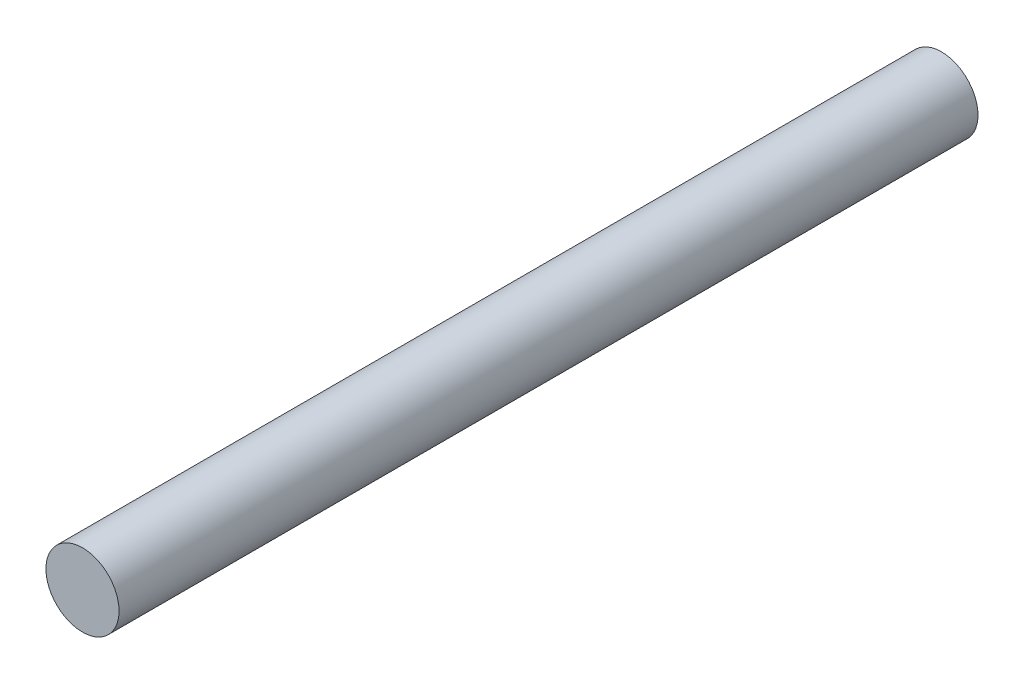
SolidWorks part; units mm, degrees
ref_plane "Front Plane" through (0, 0, 0) normal (0, 0, 1) x (1, 0, 0)
ref_plane "Top Plane" through (0, 0, 0) normal (0, 1, 0) x (1, 0, 0)
ref_plane "Right Plane" through (0, 0, 0) normal (1, 0, 0) x (0, 0, -1)
sketch "Sketch1" plane through (0, 0, 0) normal (0, 0, 1) x (1, 0, 0)
  circle A0 centre (0, 0) radius 1.5875
  dimension "D1" = 3.175
extrude "Boss-Extrude1" add sketch "Sketch1" along normal blind 37.3062
